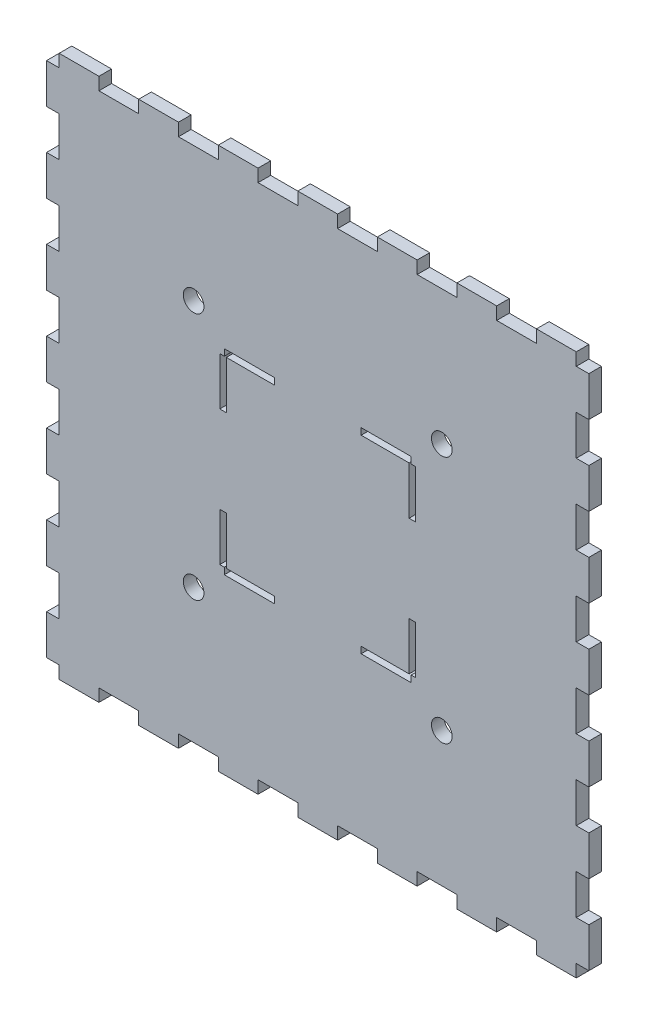
SolidWorks part; units mm, degrees
ref_plane "Front Plane" through (0, 0, 0) normal (0, 0, 1) x (1, 0, 0)
ref_plane "Top Plane" through (0, 0, 0) normal (0, 1, 0) x (1, 0, 0)
ref_plane "Right Plane" through (0, 0, 0) normal (1, 0, 0) x (0, 0, -1)
sketch "Sketch2" plane through (0, 0, 0) normal (0, 0, 1) x (1, 0, 0)
  line L0 (125, 250) -> (125, 0) construction
  line L1 (0, 0) -> (250, 0)
  line L2 (0, 0) -> (0, 250)
  line L3 (0, 250) -> (250, 250)
  line L4 (250, 0) -> (250, 250)
  line L5 (80.825, 169.175) -> (169.175, 169.175) construction
  line L6 (80.825, 169.175) -> (80.825, 80.825) construction
  line L7 (80.825, 80.825) -> (169.175, 80.825) construction
  line L8 (169.175, 169.175) -> (169.175, 80.825) construction
  line L9 (0, 125) -> (250, 125) construction
  line L10 (0, 250) -> (0, 256.096)
  line L19 (169.175, 80.825) -> (172.35, 80.825)
  line L20 (169.175, 80.825) -> (169.175, 104)
  line L21 (169.175, 104) -> (172.35, 104)
  line L22 (172.35, 80.825) -> (172.35, 104)
  line L23 (169.175, 80.825) -> (146, 80.825)
  line L25 (169.175, 77.65) -> (146, 77.65)
  line L26 (146, 80.825) -> (146, 77.65)
  line L31 (80.825, 80.825) -> (77.65, 80.825)
  line L32 (80.825, 80.825) -> (80.825, 104)
  line L33 (80.825, 104) -> (77.65, 104)
  line L34 (77.65, 80.825) -> (77.65, 104)
  line L35 (169.175, 169.175) -> (172.35, 169.175)
  line L36 (169.175, 169.175) -> (169.175, 146)
  line L37 (169.175, 146) -> (172.35, 146)
  line L38 (172.35, 169.175) -> (172.35, 146)
  line L39 (80.825, 169.175) -> (77.65, 169.175)
  line L40 (80.825, 169.175) -> (80.825, 146)
  line L41 (80.825, 146) -> (77.65, 146)
  line L42 (77.65, 169.175) -> (77.65, 146)
  line L43 (0, 256.096) -> (19.2308, 256.096)
  line L44 (19.2308, 256.096) -> (19.2308, 250)
  line L45 (38.4615, 256.096) -> (57.6923, 256.096)
  line L46 (57.6923, 256.096) -> (57.6923, 250)
  line L47 (38.4615, 250) -> (38.4615, 256.096)
  line L48 (76.9231, 256.096) -> (96.1538, 256.096)
  line L49 (96.1538, 256.096) -> (96.1538, 250)
  line L50 (76.9231, 250) -> (76.9231, 256.096)
  line L51 (115.3846, 256.096) -> (134.6154, 256.096)
  line L52 (134.6154, 256.096) -> (134.6154, 250)
  line L53 (115.3846, 250) -> (115.3846, 256.096)
  line L54 (153.8462, 256.096) -> (173.0769, 256.096)
  line L55 (173.0769, 256.096) -> (173.0769, 250)
  line L56 (153.8462, 250) -> (153.8462, 256.096)
  line L57 (192.3077, 256.096) -> (211.5385, 256.096)
  line L58 (211.5385, 256.096) -> (211.5385, 250)
  line L59 (192.3077, 250) -> (192.3077, 256.096)
  line L60 (230.7692, 256.096) -> (250, 256.096)
  line L61 (250, 256.096) -> (250, 250)
  line L62 (230.7692, 250) -> (230.7692, 256.096)
  line L63 (211.5385, 250) -> (230.7692, 250) construction
  line L64 (250, 250) -> (250, 0)
  line L65 (250, 250) -> (256.096, 250)
  line L66 (256.096, 250) -> (256.096, 230.7692)
  line L67 (256.096, 230.7692) -> (250, 230.7692)
  line L68 (256.096, 211.5385) -> (256.096, 192.3077)
  line L69 (256.096, 192.3077) -> (250, 192.3077)
  line L70 (250, 211.5385) -> (256.096, 211.5385)
  line L71 (256.096, 173.0769) -> (256.096, 153.8462)
  line L72 (256.096, 153.8462) -> (250, 153.8462)
  line L73 (250, 173.0769) -> (256.096, 173.0769)
  line L74 (256.096, 134.6154) -> (256.096, 115.3846)
  line L75 (256.096, 115.3846) -> (250, 115.3846)
  line L76 (250, 134.6154) -> (256.096, 134.6154)
  line L77 (256.096, 96.1538) -> (256.096, 76.9231)
  line L78 (256.096, 76.9231) -> (250, 76.9231)
  line L79 (250, 96.1538) -> (256.096, 96.1538)
  line L80 (256.096, 57.6923) -> (256.096, 38.4615)
  line L81 (256.096, 38.4615) -> (250, 38.4615)
  line L82 (250, 57.6923) -> (256.096, 57.6923)
  line L83 (256.096, 19.2308) -> (256.096, 0)
  line L84 (256.096, 0) -> (250, 0)
  line L85 (250, 19.2308) -> (256.096, 19.2308)
  line L86 (250, 38.4615) -> (250, 19.2308) construction
  line L87 (250, 0) -> (0, 0)
  line L88 (250, 0) -> (250, -6.096)
  line L89 (250, -6.096) -> (230.7692, -6.096)
  line L90 (230.7692, -6.096) -> (230.7692, 0)
  line L91 (211.5385, -6.096) -> (192.3077, -6.096)
  line L92 (192.3077, -6.096) -> (192.3077, 0)
  line L93 (211.5385, 0) -> (211.5385, -6.096)
  line L94 (173.0769, -6.096) -> (153.8462, -6.096)
  line L95 (153.8462, -6.096) -> (153.8462, 0)
  line L96 (173.0769, 0) -> (173.0769, -6.096)
  line L97 (134.6154, -6.096) -> (115.3846, -6.096)
  line L98 (115.3846, -6.096) -> (115.3846, 0)
  line L99 (134.6154, 0) -> (134.6154, -6.096)
  line L100 (96.1538, -6.096) -> (76.9231, -6.096)
  line L101 (76.9231, -6.096) -> (76.9231, 0)
  line L102 (96.1538, 0) -> (96.1538, -6.096)
  line L103 (57.6923, -6.096) -> (38.4615, -6.096)
  line L104 (38.4615, -6.096) -> (38.4615, 0)
  line L105 (57.6923, 0) -> (57.6923, -6.096)
  line L106 (19.2308, -6.096) -> (0, -6.096)
  line L107 (0, -6.096) -> (0, 0)
  line L108 (19.2308, 0) -> (19.2308, -6.096)
  line L109 (38.4615, 0) -> (19.2308, 0) construction
  line L110 (0, 0) -> (0, 250)
  line L111 (0, 0) -> (-6.096, 0)
  line L112 (-6.096, 0) -> (-6.096, 19.2308)
  line L113 (-6.096, 19.2308) -> (0, 19.2308)
  line L114 (-6.096, 38.4615) -> (-6.096, 57.6923)
  line L115 (-6.096, 57.6923) -> (0, 57.6923)
  line L116 (0, 38.4615) -> (-6.096, 38.4615)
  line L117 (-6.096, 76.9231) -> (-6.096, 96.1538)
  line L118 (-6.096, 96.1538) -> (0, 96.1538)
  line L119 (0, 76.9231) -> (-6.096, 76.9231)
  line L120 (-6.096, 115.3846) -> (-6.096, 134.6154)
  line L121 (-6.096, 134.6154) -> (0, 134.6154)
  line L122 (0, 115.3846) -> (-6.096, 115.3846)
  line L123 (-6.096, 153.8462) -> (-6.096, 173.0769)
  line L124 (-6.096, 173.0769) -> (0, 173.0769)
  line L125 (0, 153.8462) -> (-6.096, 153.8462)
  line L126 (-6.096, 192.3077) -> (-6.096, 211.5385)
  line L127 (-6.096, 211.5385) -> (0, 211.5385)
  line L128 (0, 192.3077) -> (-6.096, 192.3077)
  line L129 (-6.096, 230.7692) -> (-6.096, 250)
  line L130 (-6.096, 250) -> (0, 250)
  line L131 (0, 230.7692) -> (-6.096, 230.7692)
  line L132 (0, 211.5385) -> (0, 230.7692) construction
  line L133 (169.175, 77.65) -> (170.175, 77.65)
  line L134 (170.175, 77.65) -> (170.175, 80.825)
  line L135 (169.175, 80.825) -> (146, 80.825)
  line L136 (104, 80.825) -> (104, 77.65)
  line L137 (79.825, 77.65) -> (79.825, 80.825)
  line L138 (80.825, 77.65) -> (79.825, 77.65)
  line L139 (80.825, 77.65) -> (104, 77.65)
  line L140 (104, 80.825) -> (80.825, 80.825)
  line L141 (169.175, 172.35) -> (170.175, 172.35)
  line L142 (80.825, 172.35) -> (79.825, 172.35)
  line L143 (79.825, 172.35) -> (79.825, 169.175)
  line L144 (104, 169.175) -> (80.825, 169.175)
  line L145 (80.825, 172.35) -> (104, 172.35)
  line L146 (104, 169.175) -> (104, 172.35)
  line L147 (146, 169.175) -> (146, 172.35)
  line L148 (169.175, 172.35) -> (146, 172.35)
  line L149 (169.175, 169.175) -> (146, 169.175)
  line L150 (170.175, 172.35) -> (170.175, 169.175)
  line L152 (170.175, 77.65) -> (146, 77.65)
  line L153 (170.175, 77.65) -> (170.175, 80.825)
  line L154 (170.175, 80.825) -> (146, 80.825)
  line L155 (146, 77.65) -> (146, 80.825)
  line L156 (104, 77.65) -> (79.825, 77.65)
  line L157 (104, 77.65) -> (104, 80.825)
  line L158 (104, 80.825) -> (79.825, 80.825)
  line L159 (79.825, 77.65) -> (79.825, 80.825)
  line L160 (104, 169.175) -> (79.825, 169.175)
  line L161 (104, 169.175) -> (104, 172.35)
  line L162 (104, 172.35) -> (79.825, 172.35)
  line L163 (79.825, 169.175) -> (79.825, 172.35)
  line L164 (170.175, 169.175) -> (146, 169.175)
  line L165 (170.175, 169.175) -> (170.175, 172.35)
  line L166 (170.175, 172.35) -> (146, 172.35)
  line L167 (146, 169.175) -> (146, 172.35)
  point P13 (125, 169.175)
  point P14 (80.825, 125)
  point P43 (125, 125)
  dimension "D1" = 250
  dimension "D2" = 88.35
  dimension "D3" = 3.175
  dimension "D4" = 23.175
  dimension "D6" = 6.096
  dimension "D8" = 1
  dimension "D5" = 7
  dimension "D7" = 4
extrude "Boss-Extrude2" add sketch "Sketch2" along normal blind 6.096 contours L108 L1 L107 L106 | L105 L87 L104 L103 | L102 L87 L101 L100 | L99 L87 L98 L97 | L96 L87 L95 L94 | L93 L87 L92 L91 | L90 L89 L88 L87 | L85 L4 L84 L83 | L82 L64 L81 L80 | L79 L64 L78 L77 | L76 L64 L75 L74 | L73 L64 L72 L71 | L70 L64 L69 L68 | L67 L66 L65 L64 | L62 L3 L61 L60 | L59 L3 L58 L57 | L56 L3 L55 L54 | L53 L3 L52 L51 | L50 L3 L49 L48 | L47 L3 L46 L45 | L44 L43 L10 L3 | L131 L110 L130 L129 | L128 L2 L127 L126 | L125 L110 L124 L123 | L122 L2 L121 L120 | L119 L110 L118 L117 | L116 L2 L115 L114 | L113 L112 L111 L2
sketch "Sketch3" plane through (0, 0, 0) normal (0, 0, -1) x (-1, 0, 0)
  line L0 (-125, 256.096) -> (-125, -6.096) construction
  line L1 (-115.3846, 256.096) -> (-134.6154, 256.096) construction
  line L2 (-134.6154, -6.096) -> (-115.3846, -6.096) construction
  line L3 (6.096, 125) -> (-256.096, 125) construction
  line L4 (6.096, 115.3846) -> (6.096, 134.6154) construction
  line L5 (-256.096, 134.6154) -> (-256.096, 115.3846) construction
  line L6 (-185, 185) -> (-125, 185) construction
  line L7 (-185, 185) -> (-185, 125) construction
  circle A0 centre (-185, 185) radius 5
  circle A1 centre (-65, 185) radius 5
  circle A2 centre (-65, 65) radius 5
  circle A3 centre (-185, 65) radius 5
  dimension "D1" = 10
  dimension "D2" = 60
extrude "Cut-Extrude1" cut sketch "Sketch3" against normal through all
